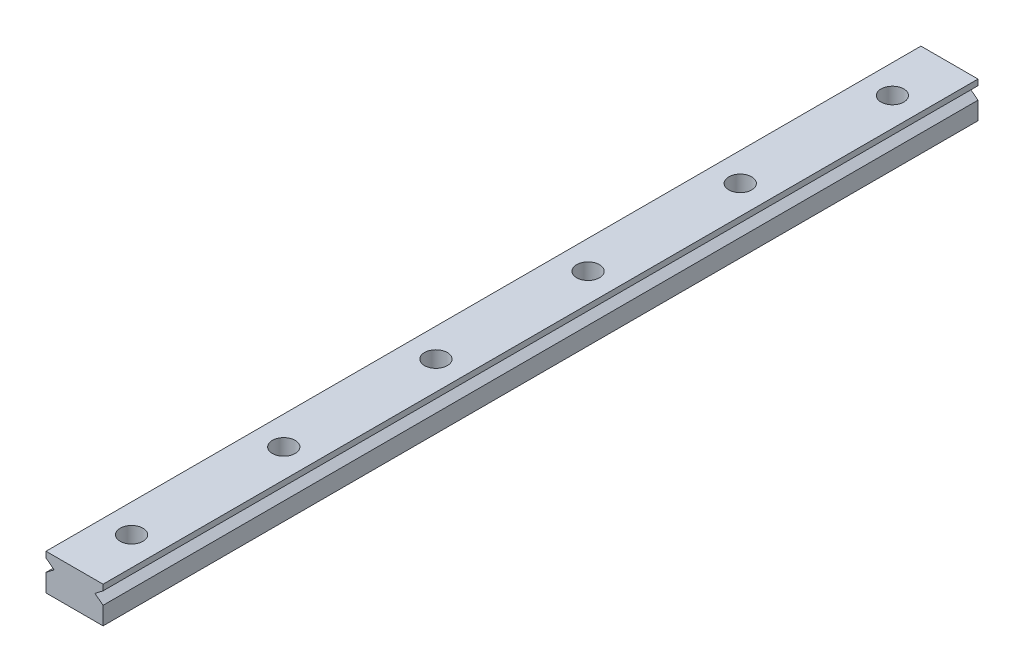
SolidWorks part; units mm, degrees
ref_plane "Front Plane" through (0, 0, 0) normal (0, 0, 1) x (1, 0, 0)
ref_plane "Top Plane" through (0, 0, 0) normal (0, 1, 0) x (1, 0, 0)
ref_plane "Right Plane" through (0, 0, 0) normal (1, 0, 0) x (0, 0, -1)
sketch "Sketch2" plane through (0, 0, 0) normal (0, 0, 1) x (1, 0, 0)
  line L0 (-7.5, 6.3333) -> (7.5, 6.3333) construction
  line L1 (-7.5, 0) -> (7.5, 0)
  line L2 (-7.5, 0) -> (-7.5, 4.6891)
  line L3 (-7.5, 9.5) -> (7.5, 9.5)
  line L4 (7.5, 0) -> (7.5, 4.6891)
  line L5 (7.5, 7.9776) -> (5.3571, 6.3333)
  line L6 (5.3571, 6.3333) -> (7.5, 4.6891)
  line L7 (7.5, 7.9776) -> (7.5, 9.5)
  line L8 (0, -0.548) -> (0, 6.6779) construction
  line L9 (-5.3571, 6.3333) -> (-7.5, 4.6891)
  line L10 (-7.5, 7.9776) -> (-5.3571, 6.3333)
  line L11 (-7.5, 7.9776) -> (-7.5, 9.5)
  dimension "Width [C]" = 15
  dimension "Height [H1]" = 9.5
  dimension "D3" = 3.1667
  dimension "D4" = 2.1429
  dimension "D5" = 75
extrude "Rail" add sketch "Sketch2" against normal blind 230
ref_plane "Plane1_Assy" through (0, 0, -115) normal (0, 0, 1) x (1, 0, 0)
sketch "Sketch6" plane through (0, 0, 0) normal (1, 0, 0) x (0, 0, -1)
  line L0 (215, 8.9049) -> (215, -3.861) construction
  line L2 (215, 9.5) -> (218, 9.5)
  line L3 (218, 9.5) -> (218, 5)
  line L4 (218, 5) -> (216.75, 5)
  line L5 (216.75, 5) -> (216.75, 0)
  line L6 (216.75, 0) -> (215, 0)
  line L7 (230, 9.5) -> (0, 9.5) construction
  line L8 (230, 0) -> (0, 0) construction
  line L9 (215, 9.5) -> (215, 0)
  line L10 (230, 0) -> (230, 4.6891) construction
  dimension "Dimension [G]" = 6
  dimension "Dimension [d]" = 3.5
  dimension "Dimension [h]" = 4.5
  dimension "End Hole Spacing [N]" = 15
revolve "C'Bore" cut sketch "Sketch6" angle 360 about L0
pattern_linear "LPattern1" count 6 spacing 40 along (0, 0, 1) of "C'Bore"
equation "\"D4@Sketch2\"=\"Width [C]@Sketch2\"/7"
equation "\"D3@Sketch2\"=\"Height [H1]@Sketch2\"/3"
equation "\"D1@Plane1_Assy\" = \"Standard rail length [L]@Rail\"/2"
